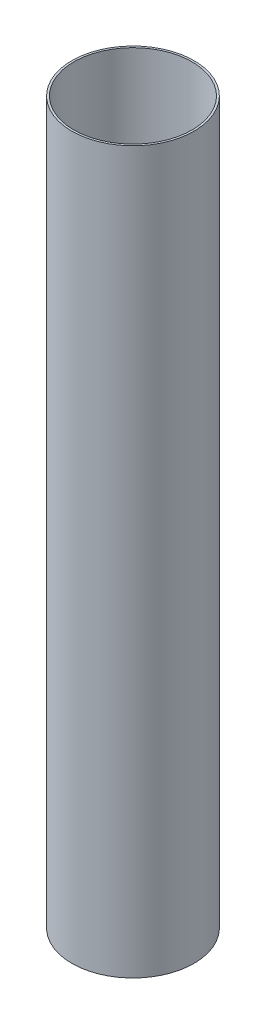
SolidWorks part; units mm, degrees
material "Hexcel AS4C (3000 Filaments)"
ref_plane "Plan de face" through (0, 0, 0) normal (0, 0, 1) x (1, 0, 0)
ref_plane "Plan de dessus" through (0, 0, 0) normal (0, 1, 0) x (1, 0, 0)
ref_plane "Plan de droite" through (0, 0, 0) normal (1, 0, 0) x (0, 0, -1)
sketch "Esquisse1" plane through (0, 0, 0) normal (0, 1, 0) x (1, 0, 0)
  circle A0 centre (0, 0) radius 76.3
  circle A1 centre (0, 0) radius 73.8
  dimension "D1" = 152.6
  dimension "D2" = 147.6
extrude "Boss.-Extru.1" add sketch "Esquisse1" along normal blind 900
